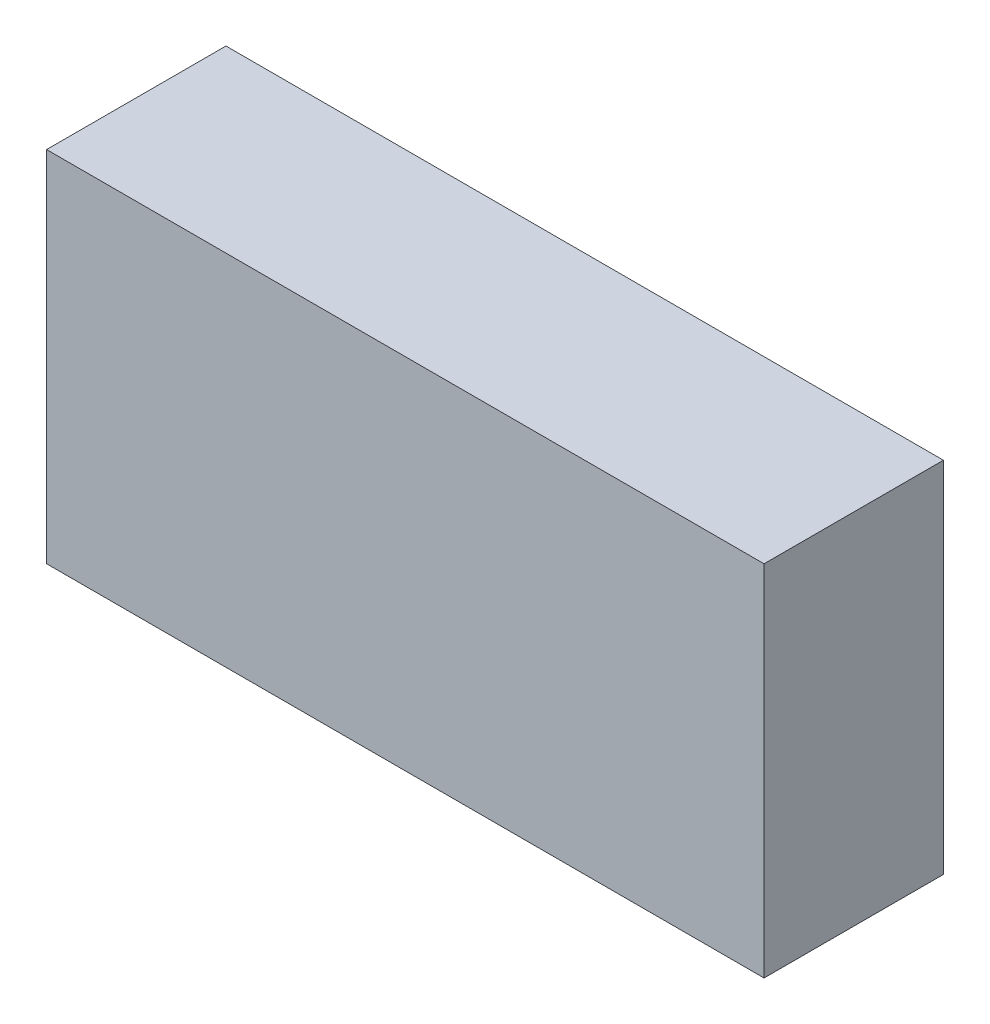
SolidWorks part; units mm, degrees
ref_plane "Front Plane" through (0, 0, 0) normal (0, 0, 1) x (1, 0, 0)
ref_plane "Top Plane" through (0, 0, 0) normal (0, 1, 0) x (1, 0, 0)
ref_plane "Right Plane" through (0, 0, 0) normal (1, 0, 0) x (0, 0, -1)
sketch "Sketch1" plane through (0, 0, 0) normal (0, 0, 1) x (1, 0, 0)
  line L1 (0, 0) -> (50.8, 0)
  line L2 (0, 0) -> (0, -25.4)
  line L3 (0, -25.4) -> (50.8, -25.4)
  line L4 (50.8, 0) -> (50.8, -25.4)
  dimension "D1" = 50.8
  dimension "D2" = 25.4
extrude "Boss-Extrude1" add sketch "Sketch1" along normal blind 12.7
